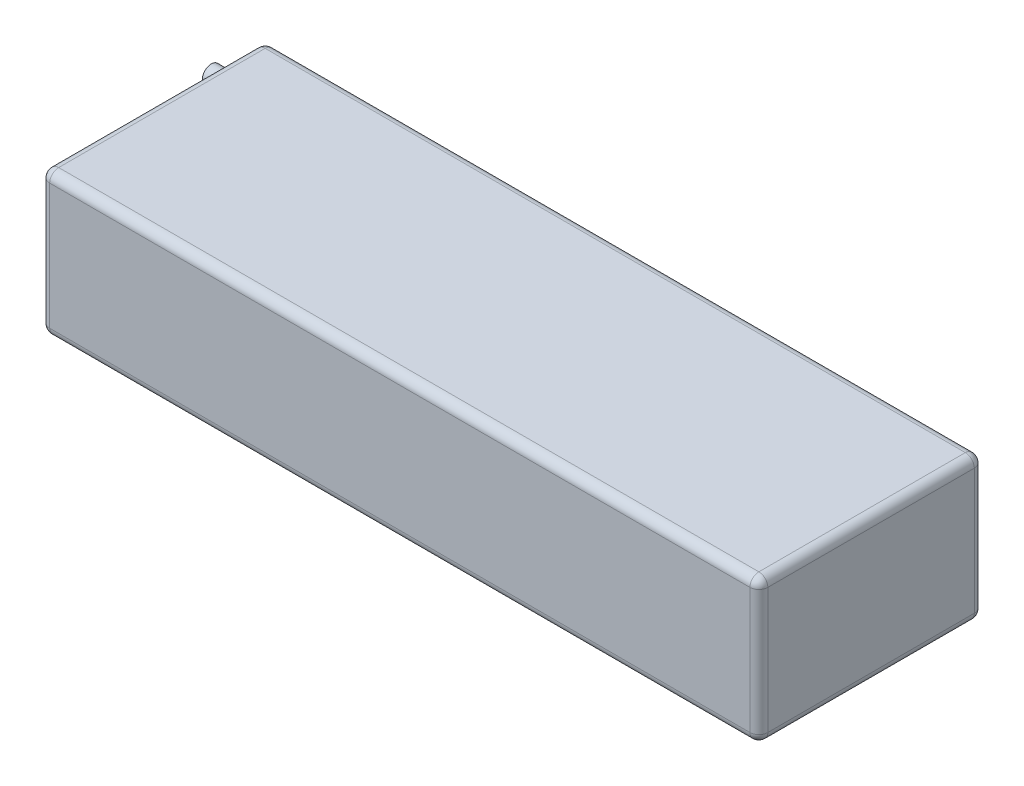
SolidWorks part; units mm, degrees
ref_plane "Front Plane" through (0, 0, 0) normal (0, 0, 1) x (1, 0, 0)
ref_plane "Top Plane" through (0, 0, 0) normal (0, 1, 0) x (1, 0, 0)
ref_plane "Right Plane" through (0, 0, 0) normal (1, 0, 0) x (0, 0, -1)
sketch "Sketch1" plane through (0, 0, 0) normal (0, 1, 0) x (1, 0, 0)
  line L1 (80, -25) -> (-80, -25)
  line L2 (80, -25) -> (80, 25)
  line L3 (80, 25) -> (-80, 25)
  line L4 (-80, -25) -> (-80, 25)
  line L5 (80, -25) -> (-80, 25) construction
  line L6 (80, 25) -> (-80, -25) construction
  point P0 (0, 0)
  dimension "D1" = 160
  dimension "D2" = 50
extrude "Boss-Extrude1" add sketch "Sketch1" along normal blind 32
fillet "Fillet1" radius 2 12 edges at (-80, 16, -25) (0, 32, -25) (-80, 32, 0) (-80, 16, 25) (0, 32, 25) (80, 16, 25) (80, 32, 0) (80, 16, -25) (0, 0, 25) (80, 0, 0) (0, 0, -25) (-80, 0, 0)
sketch "Sketch2" plane through (-80, 0, 0) normal (-1, 0, 0) x (0, 0, 1)
  line L0 (-23, 30) -> (-23, 2) construction
  line L1 (-23, 21) -> (-23, 16) construction
  line L2 (-23, 16) -> (-23, 11) construction
  circle A0 centre (-23, 21) radius 2
  circle A1 centre (-23, 16) radius 2
  circle A2 centre (-23, 11) radius 2
  dimension "D1" = 4
  dimension "D2" = 5
extrude "Boss-Extrude2" add sketch "Sketch2" along normal mid plane 20
